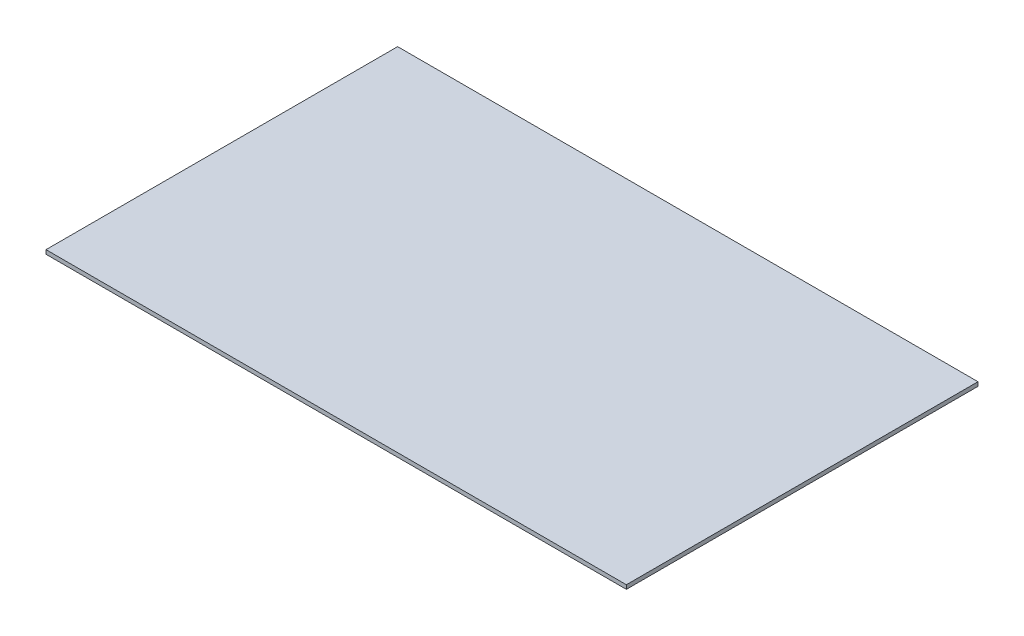
SolidWorks part; units mm, degrees
material "5052-H34"
ref_plane "Front Plane" through (0, 0, 0) normal (0, 0, 1) x (1, 0, 0)
ref_plane "Top Plane" through (0, 0, 0) normal (0, 1, 0) x (1, 0, 0)
ref_plane "Right Plane" through (0, 0, 0) normal (1, 0, 0) x (0, 0, -1)
sketch "Sketch2" plane through (0, 0, 0) normal (0, 0, 1) x (1, 0, 0)
  line L0 (0, 0) -> (458, 0)
  line L1 (0, 0) -> (0, 3.175)
  line L2 (0, 3.175) -> (458, 3.175)
  line L3 (458, 3.175) -> (458, 0)
extrude "Boss-Extrude1" add sketch "Sketch2" along normal blind 277.48 contours L2 L3 L0 L1
